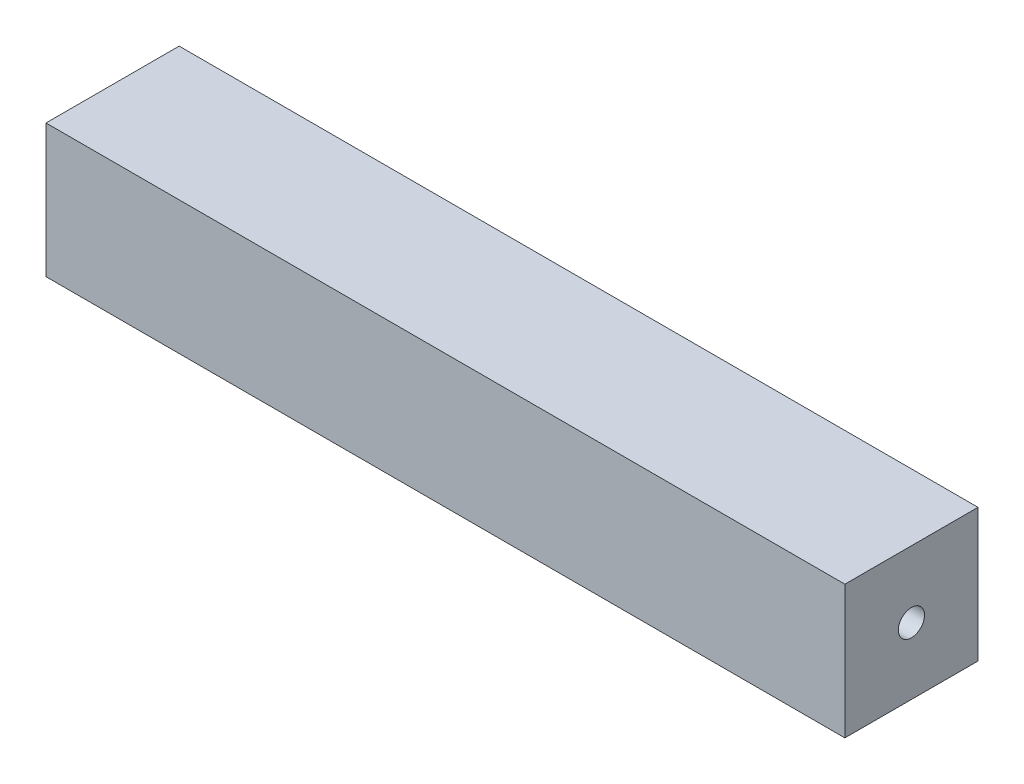
SolidWorks part; units mm, degrees
ref_plane "Front Plane" through (0, 0, 0) normal (0, 0, 1) x (1, 0, 0)
ref_plane "Top Plane" through (0, 0, 0) normal (0, 1, 0) x (1, 0, 0)
ref_plane "Right Plane" through (0, 0, 0) normal (1, 0, 0) x (0, 0, -1)
sketch "Sketch1" plane through (0, 0, 0) normal (0, 1, 0) x (1, 0, 0)
  line L1 (0, 0) -> (76.2, 0)
  line L2 (0, 0) -> (0, 12.7)
  line L3 (0, 12.7) -> (76.2, 12.7)
  line L4 (76.2, 0) -> (76.2, 12.7)
  line L5 (0, 0) -> (76.2, 12.7) construction
  line L6 (0, 12.7) -> (76.2, 0) construction
  point P4 (38.1, 6.35)
  dimension "D1" = 12.7
  dimension "D2" = 76.2
extrude "Boss-Extrude1" add sketch "Sketch1" along normal blind 12.7
sketch "Sketch2" plane through (76.2, 0, 0) normal (1, 0, 0) x (0, 0, -1)
  circle A0 centre (6.35, 6.35) radius 1.25
  dimension "D1" = 2.5
sketch "Sketch3" plane through (0, 0, 0) normal (-1, 0, 0) x (0, 0, 1)
  circle A0 centre (-6.35, 6.35) radius 1.25
  dimension "D1" = 2.5
extrude "Cut-Extrude1" cut sketch "Sketch3" against normal blind 15.24
extrude "Cut-Extrude2" cut sketch "Sketch2" against normal blind 15.24 contours A0
